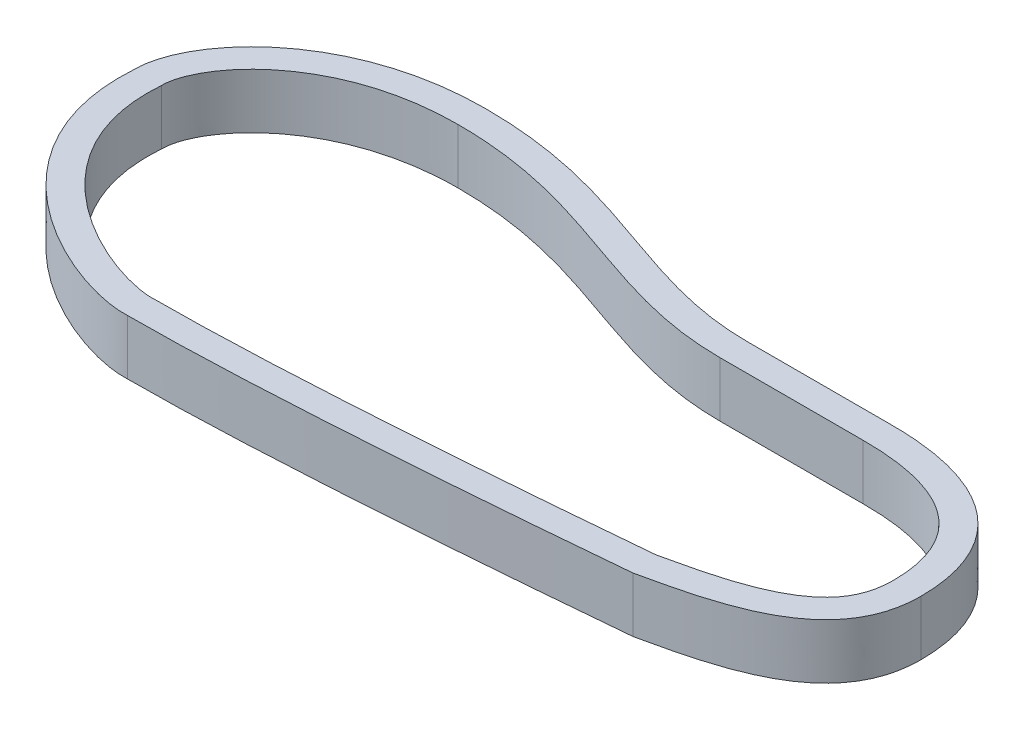
SolidWorks part; units mm, degrees
ref_plane "Front Plane" through (0, 0, 0) normal (0, 0, 1) x (1, 0, 0)
ref_plane "Top Plane" through (0, 0, 0) normal (0, 1, 0) x (1, 0, 0)
ref_plane "Right Plane" through (0, 0, 0) normal (1, 0, 0) x (0, 0, -1)
sketch "Sketch1" plane through (0, 0, 0) normal (0, 1, 0) x (1, 0, 0)
  line L0 (0, 0) -> (29.8, 0) construction
  line L1 (0, 0) -> (0, 24.3) construction
  line L2 (0, 0) -> (0, -22.5) construction
  line L3 (0, 0) -> (-86.5, 0) construction
  line L4 (-26, 0) -> (-26, 24.3) construction
  line L5 (-86.5, 0) -> (-86.5, 37.2) construction
  line L6 (-86.5, 11.6) -> (-124.6, 11.6) construction
  line L7 (-86.5, 0) -> (-86.5, -27.9) construction
  dimension "D1" = 29.8
  dimension "D2" = 24.3
  dimension "D3" = 22.5
  dimension "D4" = 26
  dimension "D5" = 86.5
  dimension "D6" = 27.9
  dimension "D7" = 37.2
  dimension "D8" = 11.6
  dimension "D9" = 38.1
sketch "Sketch2" plane through (0, 0, 0) normal (0, 1, 0) x (1, 0, 0)
  line L0 (-26, 24.3) -> (0, 24.3)
  line L1 (-124.6, 0.1449) -> (-124.6, 23.0551) construction
  line L2 (-106.5667, 37.2) -> (-66.4333, 37.2) construction
  line L3 (-42.2984, 24.3) -> (-9.7006, 24.3) construction
  line L4 (-107.4998, 37.2) -> (-65.4572, 37.2) construction
  line L5 (-64.2941, -27.9) -> (-108.7059, -27.9) construction
  line L6 (29.8, -11.2792) -> (29.8, 11.2792) construction
  line L7 (29.8, -14.0147) -> (29.8, 14.0918) construction
  spline S0 degree 3 poles (-26, 24.3) (-46.3736, 24.3) (-60.2234, 37.2) (-86.5, 37.2) knots 0 0 0 0 1 1 1 1
  spline S1 degree 3 poles (-86.5, 37.2) (-111.5833, 37.2) (-124.6, 21.1459) (-124.6, 11.6) knots 0 0 0 0 1 1 1 1
  spline S2 degree 3 poles (0, 24.3) (20.6838, 24.3847) (29.8, 14.099) (29.8, 0) knots 0 0 0 0 1 1 1 1
  spline S3 degree 3 poles (29.8, 0) (29.8, -15.9034) (12.7938, -19.6737) (0, -22.5) knots 0 0 0 0 1 1 1 1
  spline S4 degree 2 poles (-86.5, -27.9) (-58.7426, -27.9) (0, -22.5) knots 0 0 0 1 1 1
  spline S5 degree 3 poles (-124.6, 11.6) (-126.6455, -15.9296) (-96.1692, -28.4589) (-86.5, -27.9) knots 0 0 0 0 1 1 1 1
  point P0 (0, 24.3)
  point P2 (29.8, 0)
  point P4 (0, -22.5)
  point P6 (-26, 24.3)
  point P8 (-86.5, 37.2)
  point P10 (-124.6, 11.6)
  point P12 (-86.5, -27.9)
extrude "Boss-Extrude1" add sketch "Sketch2" along normal blind 10
sketch "Sketch5" plane through (0, 10, 0) normal (0, 1, 0) x (1, 0, 0)
  line L2 (0, 19.3) -> (-26, 19.3)
  line L3 (0, 19.3) -> (-26, 19.3)
  spline S10 degree 3 poles (794.3178, 2896.6346) (236.5633, 295.2684) (75.1344, 4.3942) (-36.2999, 20.219) (-38.8232, 20.7499) (-43.8284, 22.0533) (-46.3131, 22.8262) (-51.2444, 24.4704) (-53.694, 25.3411) (-58.6071, 27.0407) (-61.0707, 27.8688) (-64.8063, 28.9893) (-66.0595, 29.343) (-68.5722, 29.9962) (-69.8324, 30.2958) (-73.6263, 31.1023) (-76.1734, 31.5152) (-394.4154, 65.5197) (-1008.6606, -1988.9699) (-1423.0021, -2645.3199) knots -5.207716 -5.207716 -5.207716 -5.207716 0.125 0.125 0.25 0.25 0.375 0.375 0.5 0.5 0.625 0.625 0.6875 0.6875 0.75 0.75 0.875 0.875 16.247306 16.247306 16.247306 16.247306 only from (-26, 19.3) to (-86.5, 32.2)
  spline S11 degree 3 poles (-155.0275, 3009.7498) (283.9644, -579.3508) (39.2092, 61.7589) (-97.8181, 30.8894) (-98.6695, 30.6698) (-100.363, 30.1729) (-101.2079, 29.8946) (-103.7072, 28.973) (-105.3145, 28.249) (-108.4025, 26.5648) (-109.8852, 25.604) (-112.6954, 23.4124) (-113.9894, 22.2093) (-115.7364, 20.2177) (-116.2861, 19.5225) (-117.3076, 18.0567) (-117.7719, 17.2971) (-118.3806, 16.1123) (-118.5688, 15.7095) (-118.9104, 14.8853) (-119.0639, 14.463) (-119.321, 13.6124) (-119.4258, 13.1825) (-119.5345, 12.528) (-119.5626, 12.3083) (-119.5889, 11.9755) (-119.595, 11.8641) (-119.8529, 2.1663) (-91.4737, -13.0524) (-3067.996, 562.8701) knots -9.69525 -9.69525 -9.69525 -9.69525 0.25 0.25 0.3125 0.3125 0.375 0.375 0.5 0.5 0.625 0.625 0.75 0.75 0.8125 0.8125 0.875 0.875 0.90625 0.90625 0.9375 0.9375 0.96875 0.96875 0.984375 0.984375 0.992188 0.992188 1.660503 1.660503 1.660503 1.660503 only from (-86.5, 32.2) to (-119.6, 11.4145)
  spline S12 degree 3 poles (-3114.144, -159.344) (-75.3215, 65.211) (-118.2824, 36.1888) (-119.6695, 10.3135) (-119.7026, 9.4894) (-119.7017, 8.668) (-119.6533, 7.0291) (-119.5587, 5.9417) (-119.3168, 4.3187) (-119.2195, 3.7791) (-118.9903, 2.7027) (-118.8578, 2.164) (-118.4114, 0.5683) (-118.0496, -0.4661) (-117.2048, -2.4791) (-116.7219, -3.4578) (-115.911, -4.8862) (-115.6263, -5.3557) (-115.0287, -6.2817) (-114.7151, -6.739) (-113.0981, -8.9672) (-111.6366, -10.5868) (-109.2434, -12.8211) (-108.4118, -13.5331) (-107.1168, -14.5549) (-106.6765, -14.8883) (-105.787, -15.5353) (-105.3374, -15.8493) (-103.0661, -17.3743) (-101.1758, -18.4523) (-98.2376, -19.8702) (-97.2408, -20.3092) (-95.21, -21.1148) (-94.1746, -21.4822) (-92.0643, -22.1268) (-91.001, -22.402) (-89.3879, -22.7093) (-88.8471, -22.7942) (-88.0288, -22.8795) (-87.7547, -22.9009) (-87.3409, -22.9165) (-87.2025, -22.919) (-75.8543, -22.7912) (-57.6729, 17.6935) (-565.1077, -2984.244) knots -1.438804 -1.438804 -1.438804 -1.438804 0.015625 0.015625 0.03125 0.0625 0.0625 0.125 0.125 0.15625 0.15625 0.1875 0.1875 0.25 0.25 0.3125 0.3125 0.34375 0.34375 0.375 0.375 0.5 0.5 0.5625 0.5625 0.59375 0.59375 0.625 0.625 0.75 0.75 0.8125 0.8125 0.875 0.875 0.9375 0.9375 0.96875 0.96875 0.984375 0.984375 0.992187 0.992187 1.621629 1.621629 1.621629 1.621629 only from (-119.6, 11.4145) to (-86.6438, -22.9)
  spline S13 degree 3 poles (-743.0619, 2883.7324) (-404.1471, 44.7095) (-237.6226, -27.3739) (-72.2929, -22.6309) (-68.7098, -22.4892) (-57.9653, -21.9864) (-50.8087, -21.5494) (-36.5025, -20.5633) (-29.353, -20.0121) (442.1069, 18.8609) (896.2577, 220.25) (1524.6058, -2374.3013) knots -5.513822 -5.513822 -5.513822 -5.513822 0.125 0.125 0.25 0.25 0.5 0.5 0.75 0.75 16.991268 16.991268 16.991268 16.991268 only from (-86.6438, -22.9) to (-0.7711, -17.5498)
  spline S14 degree 3 poles (684.9632, -2932.2413) (-188.4077, 55.2091) (-72.0811, -37.5503) (8.73, -15.2186) (10.0645, -14.8145) (12.6997, -13.9014) (14.0008, -13.3934) (15.9119, -12.5052) (16.5421, -12.1879) (17.7844, -11.497) (18.3919, -11.1257) (19.5594, -10.3246) (20.1212, -9.8941) (20.9205, -9.1892) (21.1807, -8.9434) (21.6785, -8.4347) (21.9161, -8.1719) (22.5926, -7.3563) (22.9947, -6.7761) (23.5131, -5.8423) (23.6718, -5.5198) (23.9536, -4.8681) (24.0777, -4.5373) (24.4029, -3.5305) (24.5567, -2.8403) (31.3062, 45.0348) (-209.6675, 121.1409) (2725.17, -1306.3496) knots -7.13592 -7.13592 -7.13592 -7.13592 0.25 0.25 0.375 0.375 0.5 0.5 0.5625 0.5625 0.625 0.625 0.6875 0.6875 0.71875 0.71875 0.75 0.75 0.8125 0.8125 0.84375 0.84375 0.875 0.875 0.9375 0.9375 5.110249 5.110249 5.110249 5.110249 only from (-0.7711, -17.5498) to (24.8, 0)
  spline S15 degree 3 poles (3003.4514, 307.3213) (-329.5265, -207.9997) (38.0399, -68.0338) (24.2703, 5.1555) (24.0952, 5.8744) (23.7648, 6.9407) (23.6433, 7.2941) (23.3755, 7.9966) (23.2292, 8.3451) (22.7584, 9.3658) (22.3999, 10.019) (21.5892, 11.2682) (21.1362, 11.865) (19.6347, 13.56) (18.4892, 14.5137) (16.9097, 15.5257) (16.5854, 15.7195) (15.9298, 16.0859) (15.5982, 16.2589) (14.5926, 16.7499) (13.9081, 17.0401) (12.5153, 17.5579) (11.807, 17.7854) (10.3698, 18.1863) (9.6387, 18.36) (7.4366, 18.806) (5.959, 19.0045) (-85.4866, 26.721) (-201.9485, -238.1682) (23.3888, 3011.2925) knots -6.115667 -6.115667 -6.115667 -6.115667 0.125 0.125 0.1875 0.1875 0.21875 0.21875 0.25 0.25 0.3125 0.3125 0.375 0.375 0.5 0.5 0.53125 0.53125 0.5625 0.5625 0.625 0.625 0.6875 0.6875 0.75 0.75 0.875 0.875 8.448739 8.448739 8.448739 8.448739 only from (24.8, 0) to (0, 19.3)
  spline S16 degree 3 poles (-26, 19.3) (-28.6144, 19.3) (-31.1955, 19.4941) (-36.2999, 20.219) (-38.8232, 20.7499) (-43.8284, 22.0533) (-46.3131, 22.8262) (-51.2444, 24.4704) (-53.694, 25.3411) (-58.6071, 27.0407) (-61.0707, 27.8688) (-64.8063, 28.9893) (-66.0595, 29.343) (-68.5722, 29.9962) (-69.8324, 30.2958) (-73.6263, 31.1023) (-76.1734, 31.5152) (-81.3072, 32.0638) (-83.8939, 32.2) (-86.5, 32.2) knots 0 0 0 0 0.125 0.125 0.25 0.25 0.375 0.375 0.5 0.5 0.625 0.625 0.6875 0.6875 0.75 0.75 0.875 0.875 1 1 1 1
  spline S17 degree 3 poles (-86.5, 32.2) (-90.0477, 32.2) (-93.5393, 31.8534) (-97.8181, 30.8894) (-98.6695, 30.6698) (-100.363, 30.1729) (-101.2079, 29.8946) (-103.7072, 28.973) (-105.3145, 28.249) (-108.4025, 26.5648) (-109.8852, 25.604) (-112.6954, 23.4124) (-113.9894, 22.2093) (-115.7364, 20.2177) (-116.2861, 19.5225) (-117.3076, 18.0567) (-117.7719, 17.2971) (-118.3806, 16.1123) (-118.5688, 15.7095) (-118.9104, 14.8853) (-119.0639, 14.463) (-119.321, 13.6124) (-119.4258, 13.1825) (-119.5345, 12.528) (-119.5626, 12.3083) (-119.5889, 11.9755) (-119.595, 11.8641) (-119.6009, 11.64) (-119.6, 11.5271) (-119.6, 11.4145) knots 0 0 0 0 0.25 0.25 0.3125 0.3125 0.375 0.375 0.5 0.5 0.625 0.625 0.75 0.75 0.8125 0.8125 0.875 0.875 0.90625 0.90625 0.9375 0.9375 0.96875 0.96875 0.984375 0.984375 0.992188 0.992188 1 1 1 1
  spline S18 degree 3 poles (-119.6, 11.4145) (-119.6205, 11.139) (-119.64, 10.8636) (-119.6695, 10.3135) (-119.7026, 9.4894) (-119.7017, 8.668) (-119.6533, 7.0291) (-119.5587, 5.9417) (-119.3168, 4.3187) (-119.2195, 3.7791) (-118.9903, 2.7027) (-118.8578, 2.164) (-118.4114, 0.5683) (-118.0496, -0.4661) (-117.2048, -2.4791) (-116.7219, -3.4578) (-115.911, -4.8862) (-115.6263, -5.3557) (-115.0287, -6.2817) (-114.7151, -6.739) (-113.0981, -8.9672) (-111.6366, -10.5868) (-109.2434, -12.8211) (-108.4118, -13.5331) (-107.1168, -14.5549) (-106.6765, -14.8883) (-105.787, -15.5353) (-105.3374, -15.8493) (-103.0661, -17.3743) (-101.1758, -18.4523) (-98.2376, -19.8702) (-97.2408, -20.3092) (-95.21, -21.1148) (-94.1746, -21.4822) (-92.0643, -22.1268) (-91.001, -22.402) (-89.3879, -22.7093) (-88.8471, -22.7942) (-88.0288, -22.8795) (-87.7547, -22.9009) (-87.3409, -22.9165) (-87.2025, -22.919) (-86.9242, -22.9159) (-86.784, -22.9081) (-86.6438, -22.9) knots 0 0 0 0 0.015625 0.015625 0.03125 0.0625 0.0625 0.125 0.125 0.15625 0.15625 0.1875 0.1875 0.25 0.25 0.3125 0.3125 0.34375 0.34375 0.375 0.375 0.5 0.5 0.5625 0.5625 0.59375 0.59375 0.625 0.625 0.75 0.75 0.8125 0.8125 0.875 0.875 0.9375 0.9375 0.96875 0.96875 0.984375 0.984375 0.992187 0.992187 1 1 1 1
  spline S19 degree 3 poles (-86.6438, -22.9) (-83.0517, -22.9018) (-79.4639, -22.8367) (-72.2929, -22.6309) (-68.7098, -22.4892) (-57.9653, -21.9864) (-50.8087, -21.5494) (-36.5025, -20.5633) (-29.353, -20.0121) (-15.0588, -18.8335) (-7.9141, -18.2056) (-0.7711, -17.5498) knots 0 0 0 0 0.125 0.125 0.25 0.25 0.5 0.5 0.75 0.75 1 1 1 1
  spline S20 degree 3 poles (-0.7711, -17.5498) (1.9633, -16.9454) (4.6953, -16.3336) (8.73, -15.2186) (10.0645, -14.8145) (12.6997, -13.9014) (14.0008, -13.3934) (15.9119, -12.5052) (16.5421, -12.1879) (17.7844, -11.497) (18.3919, -11.1257) (19.5594, -10.3246) (20.1212, -9.8941) (20.9205, -9.1892) (21.1807, -8.9434) (21.6785, -8.4347) (21.9161, -8.1719) (22.5926, -7.3563) (22.9947, -6.7761) (23.5131, -5.8423) (23.6718, -5.5198) (23.9536, -4.8681) (24.0777, -4.5373) (24.4029, -3.5305) (24.5567, -2.8403) (24.756, -1.4273) (24.8, -0.7143) (24.8, 0) knots 0 0 0 0 0.25 0.25 0.375 0.375 0.5 0.5 0.5625 0.5625 0.625 0.625 0.6875 0.6875 0.71875 0.71875 0.75 0.75 0.8125 0.8125 0.84375 0.84375 0.875 0.875 0.9375 0.9375 1 1 1 1
  spline S21 degree 3 poles (24.8, 0) (24.8, 1.4998) (24.6799, 2.9783) (24.2703, 5.1555) (24.0952, 5.8744) (23.7648, 6.9407) (23.6433, 7.2941) (23.3755, 7.9966) (23.2292, 8.3451) (22.7584, 9.3658) (22.3999, 10.019) (21.5892, 11.2682) (21.1362, 11.865) (19.6347, 13.56) (18.4892, 14.5137) (16.9097, 15.5257) (16.5854, 15.7195) (15.9298, 16.0859) (15.5982, 16.2589) (14.5926, 16.7499) (13.9081, 17.0401) (12.5153, 17.5579) (11.807, 17.7854) (10.3698, 18.1863) (9.6387, 18.36) (7.4366, 18.806) (5.959, 19.0045) (2.9895, 19.2551) (1.4975, 19.3061) (0, 19.3) knots 0 0 0 0 0.125 0.125 0.1875 0.1875 0.21875 0.21875 0.25 0.25 0.3125 0.3125 0.375 0.375 0.5 0.5 0.53125 0.53125 0.5625 0.5625 0.625 0.625 0.6875 0.6875 0.75 0.75 0.875 0.875 1 1 1 1
  dimension "D1" = 5
extrude "Cut-Extrude2" cut sketch "Sketch5" against normal through all
sketch "Sketch3" plane through (0, 10, 0) normal (0, 1, 0) x (1, 0, 0)
  line L0 (0, 0) -> (-59.9237, 0) construction
  line L1 (0, 0) -> (-86.5, 0) construction
  line L2 (-59.9237, 0) -> (-86.5, 13.95) construction
  line L3 (-86.5, 0) -> (-86.5, 37.2) construction
  line L4 (-86.5, 13.95) -> (-86.5, -13.95) construction
  line L5 (-86.5, 0) -> (-86.5, -27.9) construction
  line L6 (-86.5, -13.95) -> (-59.9237, 0) construction
  line L8 (0, 43.3221) -> (48.2566, 43.3221)
  line L9 (0, 43.3221) -> (0, -43.3221)
  line L10 (0, -43.3221) -> (48.2566, -43.3221)
  line L11 (48.2566, 43.3221) -> (48.2566, -43.3221)
  spline S0 degree 3 poles (-86.5, -13.95) (-91.9618, -6.4228) (-91.7175, 8.0405) (-86.5, 13.95) knots 0 0 0 0 1 1 1 1
  spline S1 degree 2 poles (-86.5, 13.95) (-33.3474, 0) (-86.5, -13.95) knots 0 0 0 1 1 1
extrude "Cut-Extrude1" [suppressed] cut sketch "Sketch3" against normal through all
